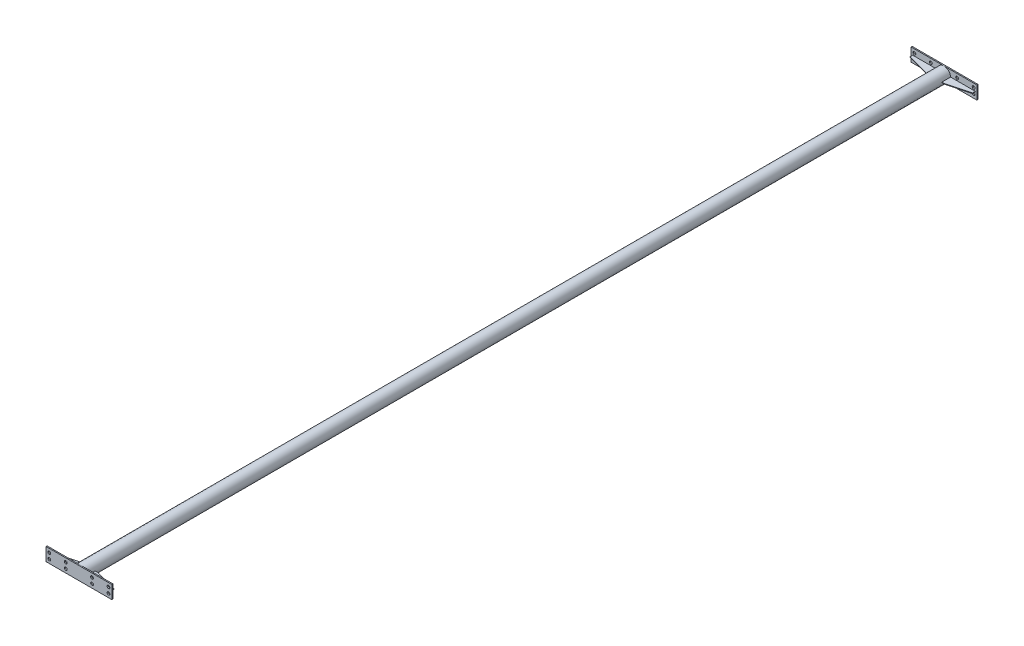
SolidWorks part; units mm, degrees
material "Plain Carbon Steel"
ref_plane "Front Plane" through (0, 0, 0) normal (0, 0, 1) x (1, 0, 0)
ref_plane "Top Plane" through (0, 0, 0) normal (0, 1, 0) x (1, 0, 0)
ref_plane "Right Plane" through (0, 0, 0) normal (1, 0, 0) x (0, 0, -1)
sketch "Sketch1" plane through (0, 0, 0) normal (0, 0, 1) x (1, 0, 0)
  line L1 (-300, -60) -> (300, -60)
  line L2 (-300, -60) -> (-300, 60)
  line L3 (-300, 60) -> (300, 60)
  line L4 (300, -60) -> (300, 60)
  line L5 (-300, -60) -> (300, 60) construction
  line L6 (-300, 60) -> (300, -60) construction
  point P0 (0, 0)
  dimension "D1" = 120
  dimension "D2" = 600
extrude "Boss-Extrude1" add sketch "Sketch1" along normal blind 10
sketch "Sketch2" plane through (0, 0, 10) normal (0, 0, 1) x (1, 0, 0)
  line L0 (300, 60) -> (-300, 60) construction
  circle A0 centre (0, 0) radius 60
extrude "Boss-Extrude2" add sketch "Sketch2" along normal blind 7880 separate body
sketch "Sketch4" plane through (0, 0, 0) normal (0, 1, 0) x (1, 0, 0)
  line L0 (285, -10) -> (285, -35)
  line L1 (300, -10) -> (-300, -10) construction
  line L2 (285, -35) -> (85, -88.5898)
  line L3 (85, -88.5898) -> (60, -88.5898)
  line L4 (60, -7890) -> (60, -10) construction
  line L5 (60, -88.5898) -> (60, -10)
  line L6 (60, -10) -> (285, -10)
  line L7 (300, -10) -> (300, 0) construction
  line L8 (0, 0) -> (0, 133.0079) construction
  line L9 (-60, -10) -> (-285, -10)
  line L10 (-60, -88.5898) -> (-60, -10)
  line L11 (-85, -88.5898) -> (-60, -88.5898)
  line L12 (-285, -35) -> (-85, -88.5898)
  line L13 (-285, -10) -> (-285, -35)
  dimension "D1" = 15
  dimension "D2" = 25
  dimension "D3" = 25
  dimension "D4" = 15
extrude "Boss-Extrude3" add sketch "Sketch4" along normal mid plane 5 separate body
ref_plane "Plane1" through (0, 0, 3950) normal (0, 0, -1) x (-1, 0, 0)
mirror "Mirror1" about plane through (0, 0, 3950) normal (0, 0, -1) of bodies 101 104 103
sketch "Sketch6" plane through (0, 0, 3950) normal (0, 0, -1) x (-1, 0, 0)
  line L0 (0, 0) -> (0, 169.6645) construction
  line L1 (-300, 60) -> (300, 60) construction
  line L2 (300, -60) -> (-300, -60) construction
  line L3 (300, 60) -> (300, -60) construction
  circle A0 centre (270, 25) radius 13
  circle A1 centre (270, -25) radius 13
  circle A2 centre (120, 25) radius 13
  circle A3 centre (120, -25) radius 13
  circle A4 centre (-120, -25) radius 13
  circle A5 centre (-120, 25) radius 13
  circle A6 centre (-270, -25) radius 13
  circle A7 centre (-270, 25) radius 13
  dimension "D1" = 26
  dimension "D2" = 35
  dimension "D3" = 35
  dimension "D4" = 150
  dimension "D5" = 30
extrude "Cut-Extrude1" cut sketch "Sketch6" against normal through all both and the other way through all
